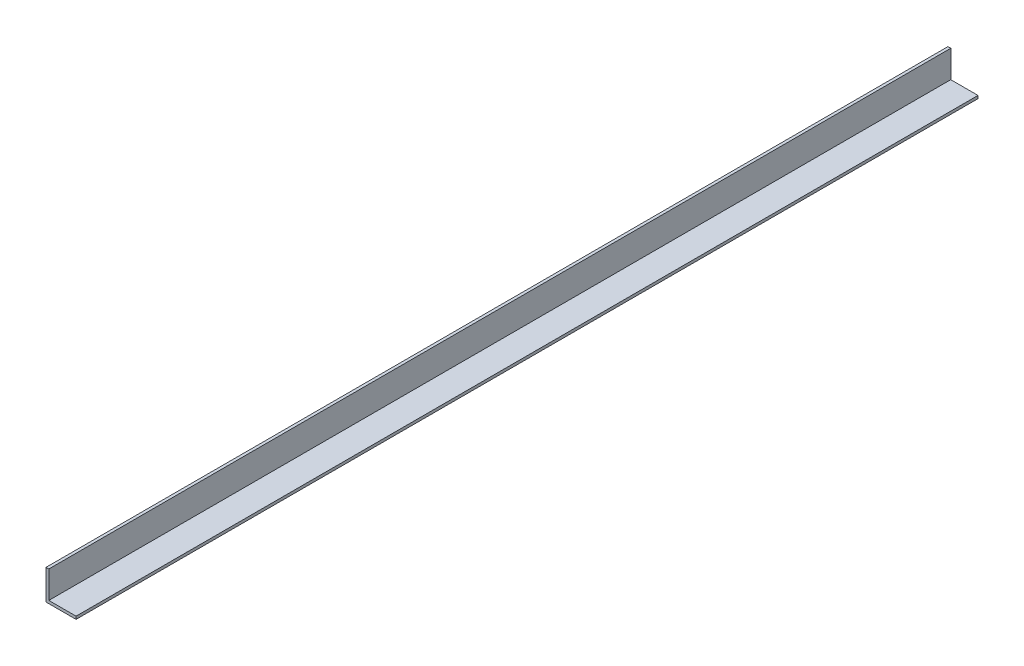
SolidWorks part; units mm, degrees
material "ASTM A36 Acero"
ref_plane "Alzado" through (0, 0, 0) normal (0, 0, 1) x (1, 0, 0)
ref_plane "Planta" through (0, 0, 0) normal (0, 1, 0) x (1, 0, 0)
ref_plane "Vista lateral" through (0, 0, 0) normal (1, 0, 0) x (0, 0, -1)
sketch "Croquis1" plane through (0, 0, 0) normal (0, 0, 1) x (1, 0, 0)
  line L0 (0, 203.3) -> (0, 0)
  line L1 (0, 0) -> (203.3, 0)
  line L2 (203.3, 0) -> (203.3, 19.05)
  line L3 (203.3, 19.05) -> (19.05, 19.05)
  line L4 (19.05, 19.05) -> (19.05, 203.3)
  line L5 (19.05, 203.3) -> (0, 203.3)
  dimension "D1" = 19.05
  dimension "D2" = 203.3
extrude "Saliente-Extruir1" add sketch "Croquis1" against normal blind 6100
